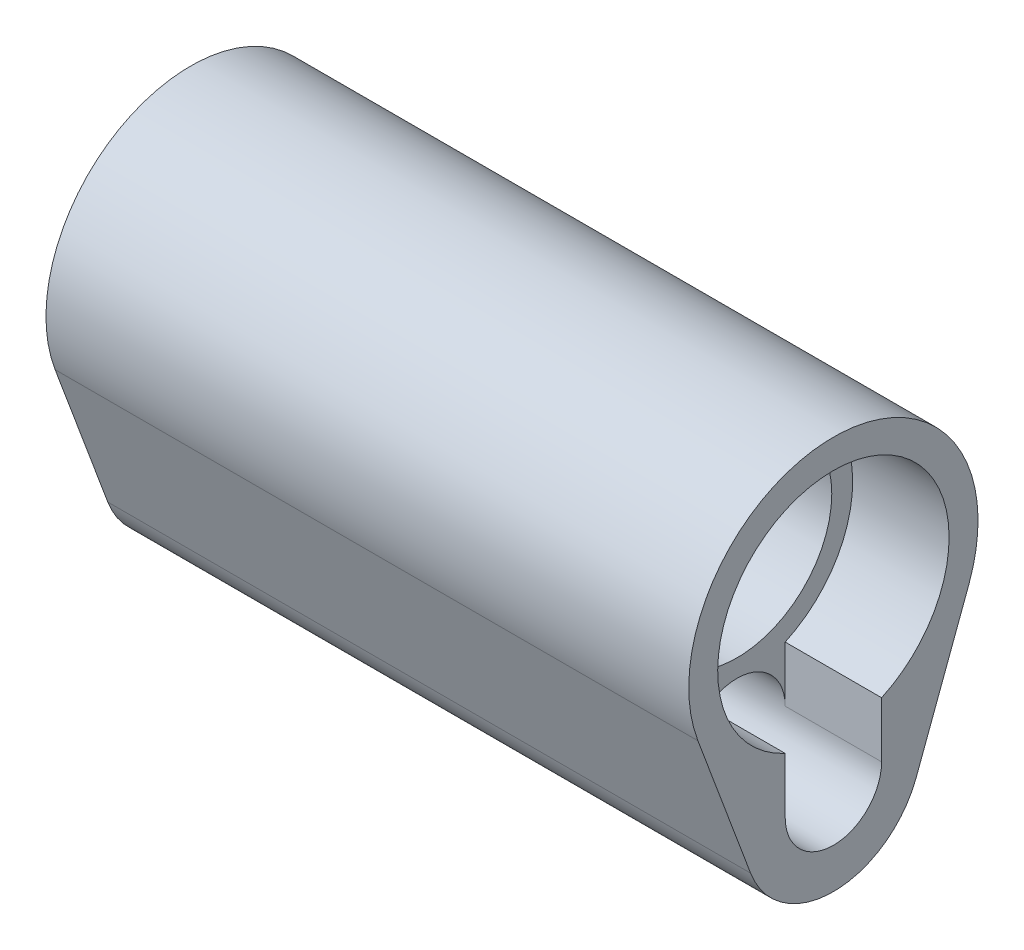
SolidWorks part; units mm, degrees
ref_plane "Спереди" through (0, 0, 0) normal (0, 0, 1) x (1, 0, 0)
ref_plane "Сверху" through (0, 0, 0) normal (0, 1, 0) x (1, 0, 0)
ref_plane "Справа" through (0, 0, 0) normal (1, 0, 0) x (0, 0, -1)
sketch "Эскиз1" plane through (0, 0, 0) normal (1, 0, 0) x (0, 0, -1)
  line L0 (0, 0) -> (0, -5) construction
  line L1 (-4.2154, -1.575) -> (-2.5761, -5.9625)
  line L3 (4.2154, -1.575) -> (2.5761, -5.9625)
  circle A0 centre (0, 0) radius 2.95
  circle A1 centre (0, -5) radius 1.5
  arc A2 (4.2154, -1.575) -> (-4.2154, -1.575) centre (0, 0) ccw
  arc A3 (-2.5761, -5.9625) -> (2.5761, -5.9625) centre (0, -5) ccw
  dimension "D1" = 5.9
  dimension "D2" = 3
  dimension "D4" = 5.5
  dimension "D5" = 9
  dimension "D3" = 5
extrude "Бобышка-Вытянуть1" add sketch "Эскиз1" along normal blind 20
sketch "Эскиз2" plane through (20, 0, 0) normal (1, 0, 0) x (0, 0, -1)
  line L1 (-1.5, -5) -> (1.5, -5)
  line L2 (-1.5, -5) -> (-1.5, -3.2726)
  line L4 (1.5, -5) -> (1.5, -3.2726)
  arc A0 (1.5, -3.2726) -> (-1.5, -3.2726) centre (0, 0) ccw
  circle A1 centre (0, -5) radius 1.5 construction
  point P1 (1.4657, -4.681)
  point P9 (1.5, -5)
  point P10 (0, -5)
  dimension "D1" = 7.2
extrude "Вырез-Вытянуть1" cut sketch "Эскиз2" against normal blind 3
